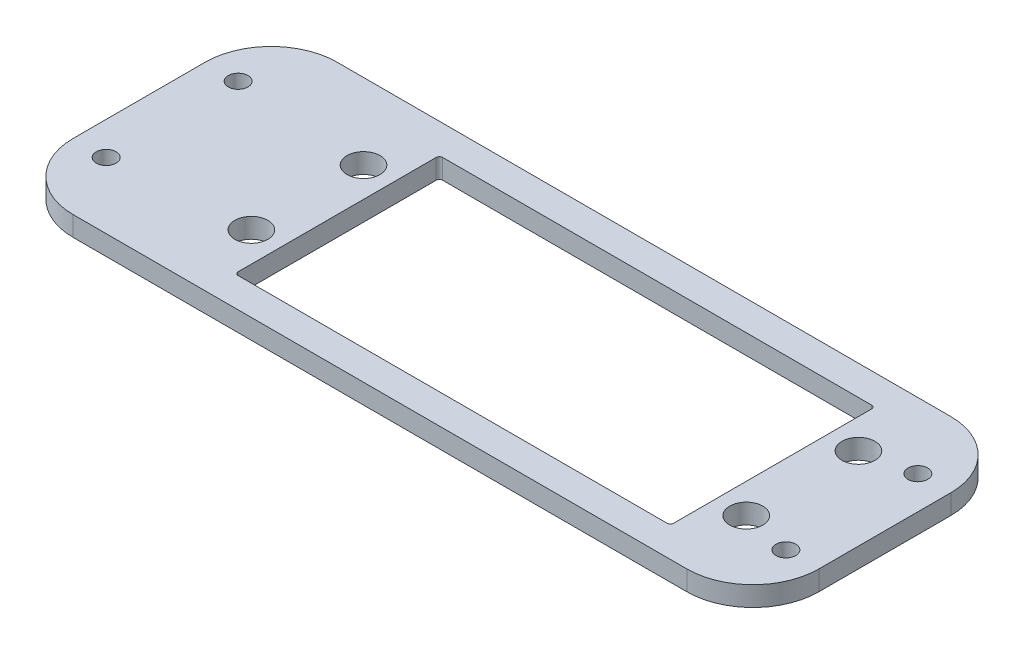
SolidWorks part; units mm, degrees
material "Thornel Mat VMA"
ref_plane "前视基准面" through (0, 0, 0) normal (0, 0, 1) x (1, 0, 0)
ref_plane "上视基准面" through (0, 0, 0) normal (0, 1, 0) x (1, 0, 0)
ref_plane "右视基准面" through (0, 0, 0) normal (1, 0, 0) x (0, 0, -1)
other "Configuration Table"
sketch "草图1" plane through (0, 0, 0) normal (0, 1, 0) x (1, 0, 0)
  line L0 (0, 0) -> (0, 29.6725) construction
  line L1 (-50, -20) -> (50, -20)
  line L2 (-50, -20) -> (-50, 20)
  line L3 (-50, 20) -> (50, 20)
  line L4 (50, -20) -> (50, 20)
  line L5 (-50, -20) -> (50, 20) construction
  line L6 (-50, 20) -> (50, -20) construction
  line L11 (-35.3528, -14.1411) -> (6.0635, 2.4254) construction
  line L12 (-50, 20) -> (-63, 20)
  line L13 (-33, -15.5) -> (33, -15.5)
  line L14 (-33, -15.5) -> (-33, 15.5)
  line L15 (-33, 15.5) -> (33, 15.5)
  line L16 (33, -15.5) -> (33, 15.5)
  line L17 (-33, -15.5) -> (33, 15.5) construction
  line L18 (-33, 15.5) -> (33, -15.5) construction
  line L19 (0, 0) -> (43.0948, 0) construction
  line L20 (-63, 20) -> (-63, -20)
  line L21 (-63, -20) -> (-50, -20)
  circle A0 centre (37.5, 8.5) radius 2.5
  circle A1 centre (37.5, -8.5) radius 2.5
  circle A2 centre (-37.5, -8.5) radius 2.5
  circle A3 centre (-37.5, 8.5) radius 2.5
  circle A4 centre (-58, 10) radius 1.5
  circle A7 centre (-58, -10) radius 1.5
  circle A8 centre (45, 10) radius 1.5
  circle A9 centre (45, -10) radius 1.5
  point P0 (0, 0)
  point P6 (0, 0)
  point P13 (0, 0)
  dimension "D5" = 5
  dimension "D8" = 3
  dimension "D11" = 3
  dimension "D1" = 100
  dimension "D2" = 40
  dimension "D3" = 66
  dimension "D4" = 31
  dimension "D6" = 8.5
  dimension "D7" = 37.5
  dimension "D9" = 58
  dimension "D10" = 10
  dimension "D12" = 45
  dimension "D13" = 10
  dimension "D14" = 13
extrude "凸台-拉伸1" add sketch "草图1" along normal blind 3 contours L1 L4 L3 L2 A3 A2 L16 L13 L14 L15 A0 A1 A8 A9 | L20 L21 L2 L12 A4 A7
fillet "圆角1" radius 0.5 4 edges at (33, 1.5, 15.5) (-33, 1.5, 15.5) (33, 1.5, -15.5) (-33, 1.5, -15.5)
fillet "圆角2" radius 10 4 edges at (50, 1.5, -20) (50, 1.5, 20) (-63, 1.5, 20) (-63, 1.5, -20)
